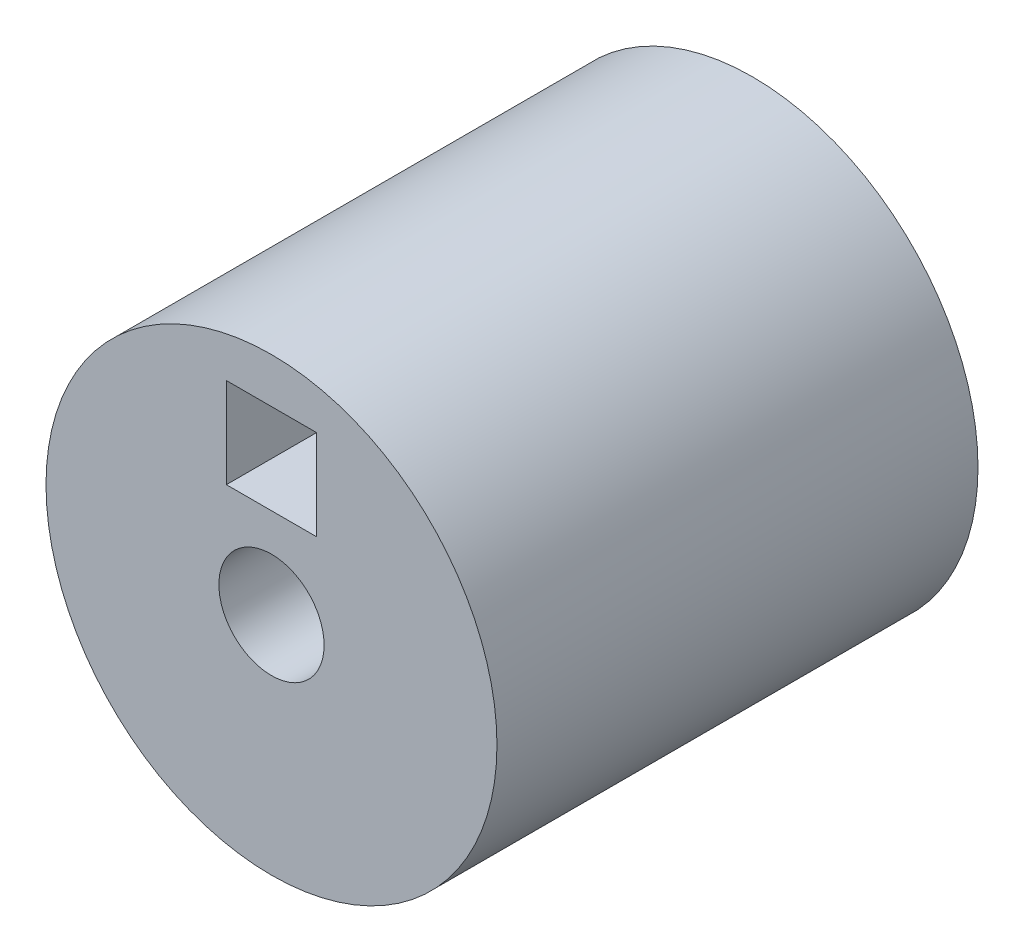
SolidWorks part; units mm, degrees
ref_plane "Front Plane" through (0, 0, 0) normal (0, 0, 1) x (1, 0, 0)
ref_plane "Top Plane" through (0, 0, 0) normal (0, 1, 0) x (1, 0, 0)
ref_plane "Right Plane" through (0, 0, 0) normal (1, 0, 0) x (0, 0, -1)
sketch "Sketch1" plane through (0, 0, 0) normal (0, 0, 1) x (1, 0, 0)
  line L0 (0, 0) -> (0, 7.5) construction
  circle A0 centre (0, 0) radius 7.5
  circle A1 centre (0, 0) radius 1.75
  circle A3 centre (0, 0) radius 3.75 construction
  dimension "D1" = 15
  dimension "D2" = 3.5
  dimension "D4" = 7.5
extrude "Boss-Extrude1" add sketch "Sketch1" along normal blind 16
sketch "Sketch2" plane through (0, 0, 16) normal (0, 0, 1) x (1, 0, 0)
  line L0 (0, 0) -> (0, 7.5) construction
  line L2 (-1.5, 3) -> (1.5, 3)
  line L3 (-1.5, 3) -> (-1.5, 6)
  line L4 (-1.5, 6) -> (1.5, 6)
  line L5 (1.5, 3) -> (1.5, 6)
  line L6 (-1.5, 3) -> (1.5, 6) construction
  line L7 (-1.5, 6) -> (1.5, 3) construction
  circle A0 centre (0, 0) radius 4.5 construction
  circle A1 centre (0, 0) radius 7.5 construction
  point P2 (0, 4.5)
  dimension "D1" = 9
  dimension "D2" = 3
  dimension "D3" = 3
extrude "Cut-Extrude1" cut sketch "Sketch2" against normal blind 8
sketch "Sketch3" plane through (0, 0, 0) normal (0, 0, -1) x (-1, 0, 0)
  line L0 (0, 0) -> (0, 4.5) construction
  line L1 (0, 0) -> (4.2798, 1.3906) construction
  line L6 (3.3167, -0.4995) -> (2.3896, 2.3536)
  line L7 (2.3896, 2.3536) -> (5.2428, 3.2807)
  line L8 (5.2428, 3.2807) -> (6.1699, 0.4275)
  line L9 (6.1699, 0.4275) -> (3.3167, -0.4995)
  line L10 (3.3167, -0.4995) -> (5.2428, 3.2807) construction
  line L11 (6.1699, 0.4275) -> (2.3896, 2.3536) construction
  circle A0 centre (0, 0) radius 4.5 construction
  point P8 (4.2798, 1.3906)
  dimension "D1" = 9
  dimension "D2" = 72
  dimension "D3" = 3
extrude "Cut-Extrude2" cut sketch "Sketch3" against normal blind 8
